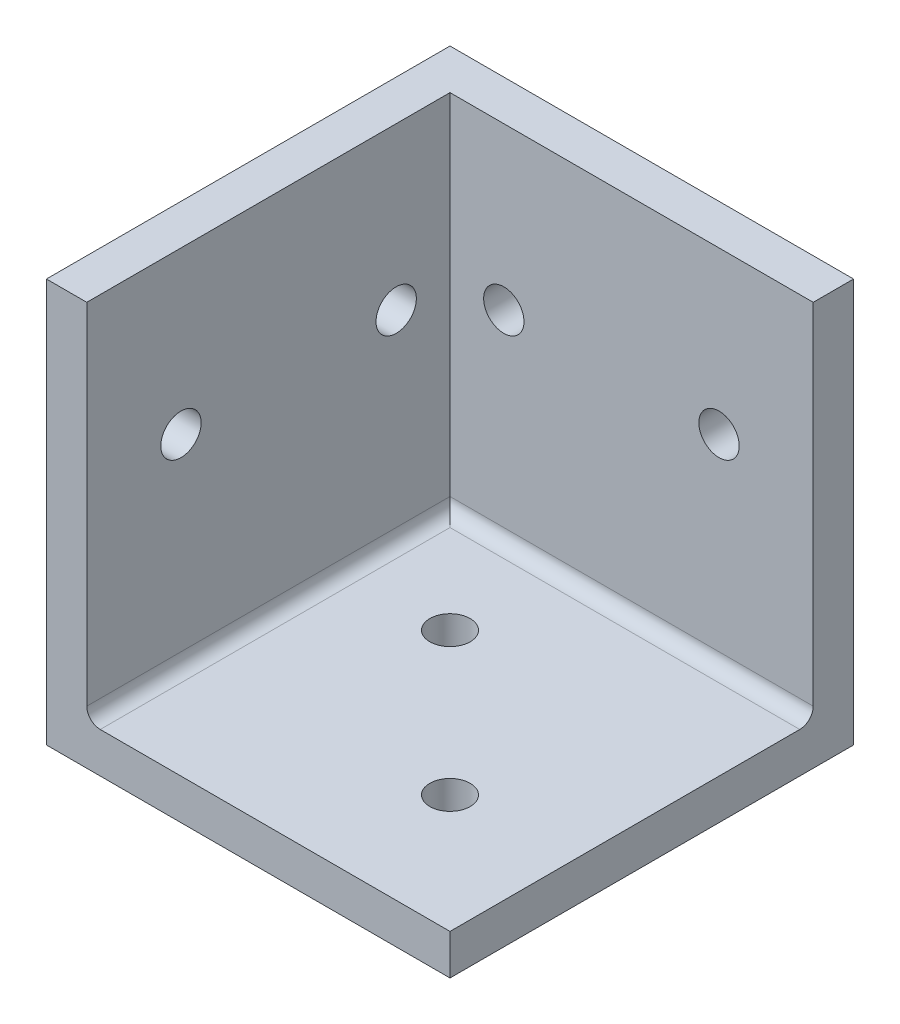
SolidWorks part; units mm, degrees
ref_plane "前视基准面" through (0, 0, 0) normal (0, 0, 1) x (1, 0, 0)
ref_plane "上视基准面" through (0, 0, 0) normal (0, 1, 0) x (1, 0, 0)
ref_plane "右视基准面" through (0, 0, 0) normal (1, 0, 0) x (0, 0, -1)
sketch "草图1" plane through (0, 0, 0) normal (0, 0, 1) x (1, 0, 0)
  line L1 (15, -15) -> (-15, -15)
  line L2 (15, -15) -> (15, 15)
  line L3 (15, 15) -> (-15, 15)
  line L4 (-15, -15) -> (-15, 15)
  line L5 (15, -15) -> (-15, 15) construction
  line L6 (15, 15) -> (-15, -15) construction
  point P0 (0, 0)
  dimension "D1" = 30
  dimension "D2" = 30
extrude "凸台-拉伸1" add sketch "草图1" along normal blind 3
sketch "草图2" plane through (0, 0, 3) normal (0, 0, 1) x (1, 0, 0)
  line L0 (0, -15) -> (0, 3) construction
  line L1 (-15, -15) -> (15, -15) construction
  line L2 (0, 3) -> (8, 3) construction
  circle A0 centre (8, 3) radius 1.5
  circle A1 centre (-8, 3) radius 1.5
  dimension "D1" = 18
  dimension "D3" = 3
  dimension "D2" = 8
extrude "切除-拉伸1" cut sketch "草图2" against normal blind 3
sketch "草图3" plane through (0, 0, 3) normal (0, 0, 1) x (1, 0, 0)
  line L0 (15, -15) -> (15, 15) construction
  line L1 (-15, -15) -> (15, -15)
  line L2 (-15, -15) -> (-15, -12)
  line L3 (-15, -12) -> (15, -12)
  line L4 (15, -15) -> (15, -12)
  dimension "D1" = 3
extrude "凸台-拉伸2" add sketch "草图3" along normal blind 27
sketch "草图4" plane through (0, -12, 0) normal (0, 1, 0) x (1, 0, 0)
  line L0 (0, -3) -> (0, -18)
  line L1 (15, -3) -> (-15, -3) construction
  line L2 (0, -18) -> (-8, -18)
  circle A0 centre (-8, -18) radius 1.5
  circle A1 centre (8, -18) radius 1.5
  dimension "D1" = 3
  dimension "D2" = 8
  dimension "D3" = 15
sketch "草图5" plane through (-15, 0, 0) normal (-1, 0, 0) x (0, 0, 1)
  line L0 (30, -12) -> (30, -15) construction
  line L1 (0, -15) -> (30, -15)
  line L2 (0, -15) -> (0, 15)
  line L3 (0, 15) -> (30, 15)
  line L4 (30, -15) -> (30, 15)
  line L5 (3, 15) -> (0, 15) construction
extrude "凸台-拉伸3" add sketch "草图5" against normal blind 3
fillet "圆角1" radius 1 2 edges at (1.5, -12, 3) (-12, -12, 16.5)
sketch "草图10" plane through (0, -15, 0) normal (0, -1, 0) x (1, 0, 0)
  line L0 (-15, 0) -> (15, 30) construction
  circle A0 centre (-4.3934, 10.6066) radius 1.5
  circle A1 centre (6.2132, 21.2132) radius 1.5
  dimension "D1" = 15
  dimension "D3" = 3
  dimension "D4" = 3
  dimension "D2" = 30
extrude "切除-拉伸4" cut sketch "草图10" against normal blind 3
sketch "草图11" plane through (-15, 0, 0) normal (-1, 0, 0) x (0, 0, 1)
  line L0 (15, -15) -> (15, 3) construction
  line L1 (30, -15) -> (0, -15) construction
  line L2 (15, 3) -> (23, 3) construction
  circle A0 centre (23, 3) radius 1.5
  circle A1 centre (7, 3) radius 1.5
  dimension "D2" = 3
  dimension "D1" = 18
  dimension "D3" = 8
extrude "切除-拉伸5" cut sketch "草图11" against normal blind 3
